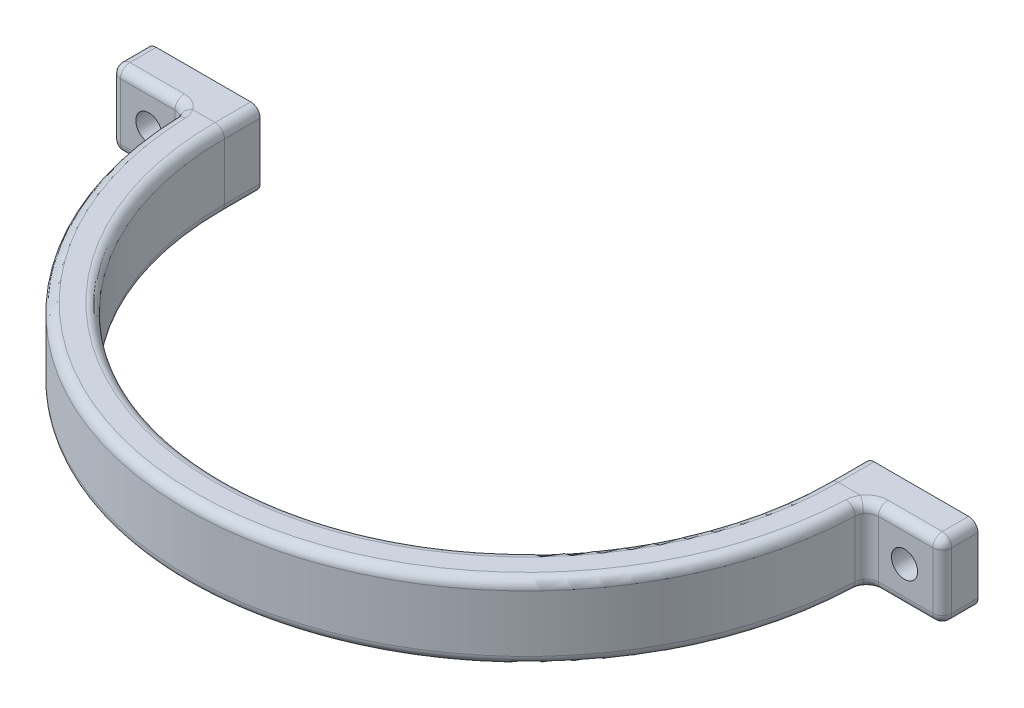
SolidWorks part; units mm, degrees
ref_plane "Front Plane" through (0, 0, 0) normal (0, 0, 1) x (1, 0, 0)
ref_plane "Top Plane" through (0, 0, 0) normal (0, 1, 0) x (1, 0, 0)
ref_plane "Right Plane" through (0, 0, 0) normal (1, 0, 0) x (0, 0, -1)
sketch "Sketch2" plane through (0, 0, 0) normal (0, 0, 1) x (1, 0, 0)
  line L1 (-34.925, -3.175) -> (-28.575, -3.175)
  line L2 (-34.925, -3.175) -> (-34.925, 3.175)
  line L3 (-34.925, 3.175) -> (-28.575, 3.175)
  line L4 (-28.575, -3.175) -> (-28.575, 3.175)
  line L5 (-34.925, -3.175) -> (-28.575, 3.175) construction
  line L6 (-34.925, 3.175) -> (-28.575, -3.175) construction
  circle A0 centre (-31.75, 0) radius 1.1
  arc A1 (-31.7372, 0.8999) -> (-31.7372, -0.8999) centre (0, 0) ccw construction
  dimension "D2" = 2.2
  dimension "D1" = 6.35
extrude "Boss-Extrude1" add sketch "Sketch2" along normal blind 3
sketch "Sketch3" plane through (0, 0, 0) normal (0, 1, 0) x (1, 0, 0)
  line L0 (-28.575, 0) -> (-28.575, -3)
  arc A0 (-28.575, -3) -> (0, -31.575) centre (0, -3) ccw
  point P5 (0, 0)
sketch "Sketch4" plane through (0, 0, 0) normal (0, 0, 1) x (1, 0, 0)
  line L0 (-34.925, -3.175) -> (-28.575, -3.175) construction
  line L1 (-28.575, 3.175) -> (-25.4, 3.175)
  line L2 (-28.575, 3.175) -> (-28.575, -3.175)
  line L3 (-28.575, -3.175) -> (-25.4, -3.175)
  line L4 (-25.4, 3.175) -> (-25.4, -3.175)
  dimension "D1" = 3.175
sweep "Sweep1" add profiles "Sketch4" path "Sketch3"
fillet "Fillet1" radius 1 1 edges at (-28.575, 0, 3)
fillet "Fillet3" radius 0.7937 13 edges at (-25.4, 3.175, 1.5) (-25.4, -3.175, 1.5) (-17.9605, 3.175, 20.9605) (-17.9605, -3.175, 20.9605) (-19.861, -3.175, 23.5443) (-28.863, -3.175, 3.281) (-19.861, 3.175, 23.5443) (-28.863, 3.175, 3.281) (-32.2415, -3.175, 3) (-34.925, 0, 3) (-34.925, 3.175, 1.5) (-34.925, -3.175, 1.5) (-32.2415, 3.175, 3)
mirror "Mirror1" about plane through (0, 0, 3) normal (1, 0, 0) of bodies 102
